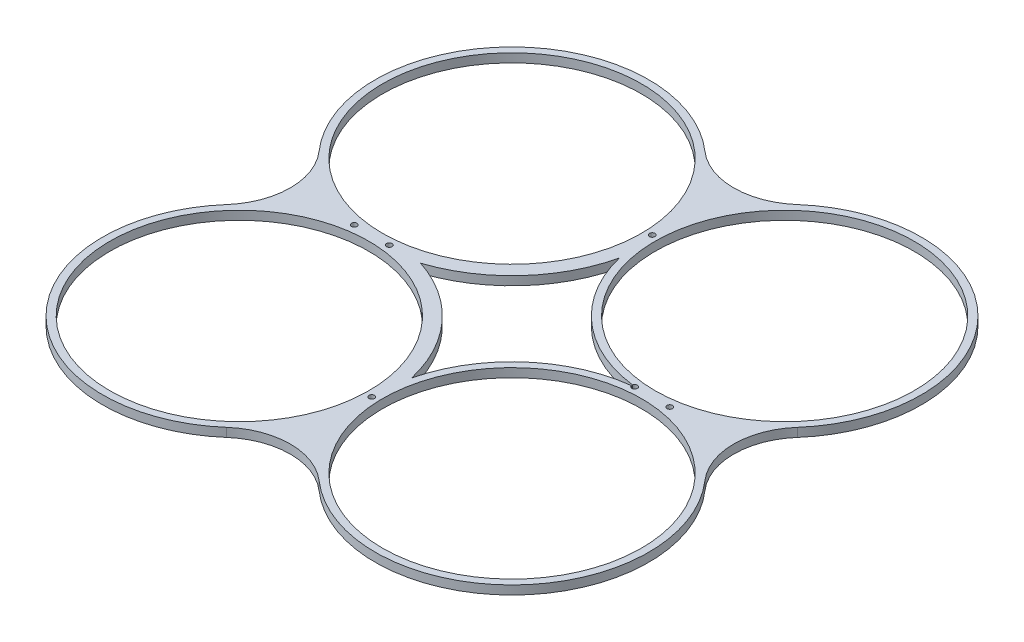
SolidWorks part; units mm, degrees
ref_plane "前视基准面" through (0, 0, 0) normal (0, 0, 1) x (1, 0, 0)
ref_plane "上视基准面" through (0, 0, 0) normal (0, 1, 0) x (1, 0, 0)
ref_plane "右视基准面" through (0, 0, 0) normal (1, 0, 0) x (0, 0, -1)
other "Configuration Table"
sketch "草图1" plane through (0, 0, 0) normal (0, 1, 0) x (1, 0, 0)
  line L0 (-40.28, 0) -> (40.28, 0) construction
  line L1 (-40.28, -50) -> (40.28, -50)
  line L2 (-40.28, -50) -> (-40.28, 50)
  line L3 (-40.28, 50) -> (40.28, 50)
  line L4 (40.28, -50) -> (40.28, 50)
  line L5 (-40.28, -50) -> (40.28, 50) construction
  line L6 (-40.28, 50) -> (40.28, -50) construction
  line L7 (0, -50) -> (0, 50) construction
  line L8 (-40.28, -50) -> (-40.28, -75.1) construction
  line L9 (-40.28, -75.1) -> (40.28, -75.1) construction
  line L10 (40.28, -75.1) -> (40.28, -50) construction
  line L11 (0, -50) -> (0, -75.1) construction
  line L12 (-40.28, -62.55) -> (40.28, -62.55) construction
  line L13 (-27, -75.1) -> (27, -75.1)
  line L14 (27, -75.1) -> (27, -50)
  line L15 (-27, -75.1) -> (-27, -50)
  circle A0 centre (-34.12, 46.89) radius 1.6
  circle A1 centre (15.09, 46.89) radius 1.6
  circle A2 centre (15.09, -40.19) radius 1.6
  circle A3 centre (-34.12, -40.19) radius 1.6
  circle A5 centre (-15.25, 15.25) radius 1.6
  circle A6 centre (15.25, 15.25) radius 1.6
  circle A7 centre (15.25, -15.25) radius 1.6
  circle A8 centre (-15.25, -15.25) radius 1.6
  circle A9 centre (14, -62.55) radius 1.6
  circle A10 centre (-14, -62.55) radius 1.6
  point P0 (0, 0)
  point P19 (0, 0)
  point P22 (0, 0)
  point P40 (0, -75.1)
  dimension "D3" = 3.2
  dimension "D10" = 3.2
  dimension "D11" = 30.5
  dimension "D12" = 30.5
  dimension "D14" = 3.2
  dimension "D1" = 80.56
  dimension "D2" = 100
  dimension "D4" = 6.16
  dimension "D5" = 3.11
  dimension "D8" = 49.21
  dimension "D9" = 87.08
  dimension "D13" = 25.1
  dimension "D15" = 28
  dimension "D16" = 54
  dimension "D6" = 2
  dimension "D7" = 2
sketch "草图6" plane through (0, 0, 0) normal (0, 1, 0) x (1, 0, 0)
  line L0 (0, 0) -> (50000, 0) construction
  line L1 (0, 0) -> (0, 50000) construction
  line L2 (-77.7817, 77.7817) -> (77.7817, 77.7817) construction
  line L3 (77.7817, 77.7817) -> (77.7817, -77.7817) construction
  line L4 (69.7817, 77.7817) -> (85.7817, 77.7817) construction
  line L5 (77.7817, 69.7817) -> (77.7817, 85.7817) construction
  line L6 (-77.7817, -77.7817) -> (77.7817, 77.7817) construction
  line L7 (77.7817, 91.5317) -> (64.0317, 77.7817)
  line L8 (91.5317, 77.7817) -> (77.7817, 64.0317)
  line L9 (-70.9067, 64.0317) -> (-40.28, 33.405)
  line L10 (-91.5317, -91.5317) -> (88.3498, 88.3498) construction
  line L11 (-87.5951, 87.5951) -> (77.7817, -77.7817) construction
  line L12 (40.28, -50) -> (40.28, 50)
  line L13 (40.28, 50) -> (-40.28, 50)
  line L14 (-40.28, 50) -> (-40.28, -50)
  line L15 (-40.28, -50) -> (40.28, -50)
  line L16 (-77.7817, 64.0317) -> (-70.9067, 64.0317)
  line L17 (-91.5317, 77.7817) -> (-77.7817, 64.0317)
  line L18 (-91.5317, 77.7817) -> (-91.5317, 85.1678)
  line L19 (-85.1678, 91.5317) -> (-91.5317, 85.1678)
  line L20 (-77.7817, 91.5317) -> (-85.1678, 91.5317)
  line L21 (77.7817, 91.5317) -> (85.1678, 91.5317)
  line L22 (91.5317, 77.7817) -> (91.5317, 85.1678)
  line L23 (-77.7817, 91.5317) -> (-64.0317, 77.7817)
  line L24 (-64.0317, 77.7817) -> (-64.0317, 70.9067)
  line L25 (72.1249, 83.4386) -> (83.4386, 72.1249) construction
  line L26 (77.7817, 64.0317) -> (70.9067, 64.0317)
  line L27 (64.0317, 77.7817) -> (64.0317, 70.9067)
  line L28 (77.7817, 64.0317) -> (70.9067, 64.0317)
  line L29 (64.0317, 77.7817) -> (64.0317, 70.9067)
  line L30 (64.0317, 70.9067) -> (40.28, 47.155)
  line L31 (70.9067, 64.0317) -> (40.28, 33.405)
  line L32 (85.1678, 91.5317) -> (91.5317, 85.1678)
  line L33 (-64.0317, 70.9067) -> (-40.28, 47.155)
  line L34 (-64.0317, -70.9067) -> (-40.28, -47.155)
  line L35 (-64.0317, -77.7817) -> (-64.0317, -70.9067)
  line L36 (-77.7817, -91.5317) -> (-64.0317, -77.7817)
  line L37 (-77.7817, -91.5317) -> (-85.1678, -91.5317)
  line L38 (-85.1678, -91.5317) -> (-91.5317, -85.1678)
  line L39 (-91.5317, -77.7817) -> (-91.5317, -85.1678)
  line L40 (-91.5317, -77.7817) -> (-77.7817, -64.0317)
  line L41 (-77.7817, -64.0317) -> (-70.9067, -64.0317)
  line L42 (-70.9067, -64.0317) -> (-40.28, -33.405)
  line L43 (70.9067, -64.0317) -> (40.28, -33.405)
  line L44 (77.7817, -64.0317) -> (70.9067, -64.0317)
  line L45 (91.5317, -77.7817) -> (77.7817, -64.0317)
  line L46 (91.5317, -77.7817) -> (91.5317, -85.1678)
  line L47 (85.1678, -91.5317) -> (91.5317, -85.1678)
  line L48 (77.7817, -91.5317) -> (85.1678, -91.5317)
  line L49 (77.7817, -91.5317) -> (64.0317, -77.7817)
  line L50 (64.0317, -77.7817) -> (64.0317, -70.9067)
  line L51 (64.0317, -70.9067) -> (40.28, -47.155)
  circle A0 centre (-77.7817, 77.7817) radius 65.9 construction
  circle A1 centre (77.7817, 77.7817) radius 65.9 construction
  circle A2 centre (-77.7817, -77.7817) radius 65.9 construction
  circle A3 centre (77.7817, -77.7817) radius 65.9 construction
  circle A4 centre (0, 0) radius 110 construction
  circle A5 centre (77.7817, 77.7817) radius 8 construction
  circle A6 centre (77.7817, 85.7817) radius 1.5
  circle A7 centre (85.7817, 77.7817) radius 1.5
  circle A8 centre (77.7817, 69.7817) radius 1.5
  circle A9 centre (69.7817, 77.7817) radius 1.5
  circle A10 centre (77.7817, 77.7817) radius 13.75 construction
  circle A11 centre (-77.7817, 85.7817) radius 1.5
  circle A12 centre (-85.7817, 77.7817) radius 1.5
  circle A13 centre (-69.7817, 77.7817) radius 1.5
  circle A14 centre (-77.7817, 69.7817) radius 1.5
  circle A15 centre (-77.7817, -69.7817) radius 1.5
  circle A16 centre (-69.7817, -77.7817) radius 1.5
  circle A17 centre (-85.7817, -77.7817) radius 1.5
  circle A18 centre (-77.7817, -85.7817) radius 1.5
  circle A19 centre (77.7817, -85.7817) radius 1.5
  circle A20 centre (85.7817, -77.7817) radius 1.5
  circle A21 centre (69.7817, -77.7817) radius 1.5
  circle A22 centre (77.7817, -69.7817) radius 1.5
  point P18 (77.7817, 77.7817)
  point P21 (77.7817, 77.7817)
  point P24 (0, 0)
  point P31 (77.7817, 77.7817)
  point P77 (77.7817, 77.7817)
sketch "草图9" plane through (0, 0, 0) normal (0, 1, 0) x (1, 0, 0)
  line L0 (0, 0) -> (50000, 0) construction
  line L1 (0, 0) -> (0, 50000) construction
  circle A0 centre (77.7817, -77.7817) radius 65.9 construction
  circle A1 centre (77.7817, 77.7817) radius 65.9 construction
  circle A2 centre (-77.7817, -77.7817) radius 65.9 construction
  circle A3 centre (-77.7817, 77.7817) radius 65.9 construction
  circle A4 centre (77.7817, -77.7817) radius 65.9 construction
  circle A5 centre (77.7817, 77.7817) radius 65.9 construction
  circle A6 centre (-77.7817, -77.7817) radius 65.9 construction
  circle A7 centre (-77.7817, 77.7817) radius 65.9 construction
  circle A8 centre (77.7817, 77.7817) radius 73.9
  circle A9 centre (-77.7817, 77.7817) radius 73.9
  circle A10 centre (-77.7817, -77.7817) radius 73.9
  circle A11 centre (77.7817, -77.7817) radius 73.9
  arc A14 (2.0044, -59.2942) -> (-52.1378, 0) centre (-77.7817, -77.7817) ccw
  circle A16 centre (0, 166.5173) radius 40 construction
  circle A17 centre (166.5173, 0) radius 40 construction
  arc A18 (2.0044, 59.2942) -> (71.9508, 0) centre (77.7817, 77.7817) ccw
  arc A19 (136.4375, 26.3667) -> (26.3667, 136.4375) centre (77.7817, 77.7817) ccw
  circle A20 centre (-77.7817, -77.7817) radius 81.9 construction
  arc A21 (71.9508, 0) -> (2.0044, -59.2942) centre (77.7817, -77.7817) ccw
  arc A23 (-52.1378, 0) -> (2.0044, 59.2942) centre (-77.7817, 77.7817) ccw
  arc A24 (-83.6127, 0) -> (-26.3667, -136.4375) centre (-77.7817, -77.7817) ccw construction
  arc A25 (-26.3667, 136.4375) -> (26.3667, 136.4375) centre (0, 166.5173) ccw
  circle A26 centre (0, 166.5173) radius 44 construction
  arc A28 (-26.3667, 136.4375) -> (-136.4375, 26.3667) centre (-77.7817, 77.7817) ccw
  arc A31 (-26.3667, -136.4375) -> (26.3667, -136.4375) centre (0, -166.5173) cw
  arc A33 (26.3667, -136.4375) -> (136.4375, -26.3667) centre (77.7817, -77.7817) ccw
  arc A34 (136.4375, 26.3667) -> (136.4375, -26.3667) centre (166.5173, 0) ccw
  arc A35 (-136.4375, 26.3667) -> (-136.4375, -26.3667) centre (-166.5173, 0) cw
  arc A36 (-136.4375, -26.3667) -> (-26.3667, -136.4375) centre (-77.7817, -77.7817) ccw
  circle A37 centre (70, 0) radius 1.6
  circle A38 centre (-70, 0) radius 1.6
  circle A39 centre (90, 0) radius 1.6
  circle A40 centre (-90, 0) radius 1.6
  circle A41 centre (0, -80) radius 1.6
  circle A42 centre (0, 80) radius 1.6
  dimension "D3" = 78
  dimension "D4" = 80
  dimension "D5" = 88
  dimension "D6" = 80
  dimension "D7" = 3.2
  dimension "D8" = 3.2
  dimension "D9" = 20
  dimension "D10" = 140
  dimension "D11" = 3.2
  dimension "D12" = 80
  dimension "D1" = 8
  dimension "D2" = 8
extrude "凸台-拉伸4" add sketch "草图9" along normal blind 5 contours A35 A36 A31 A33 A34 A19 A25 A28 A14 A23 A18 A21 A8 A9 A10 A11
